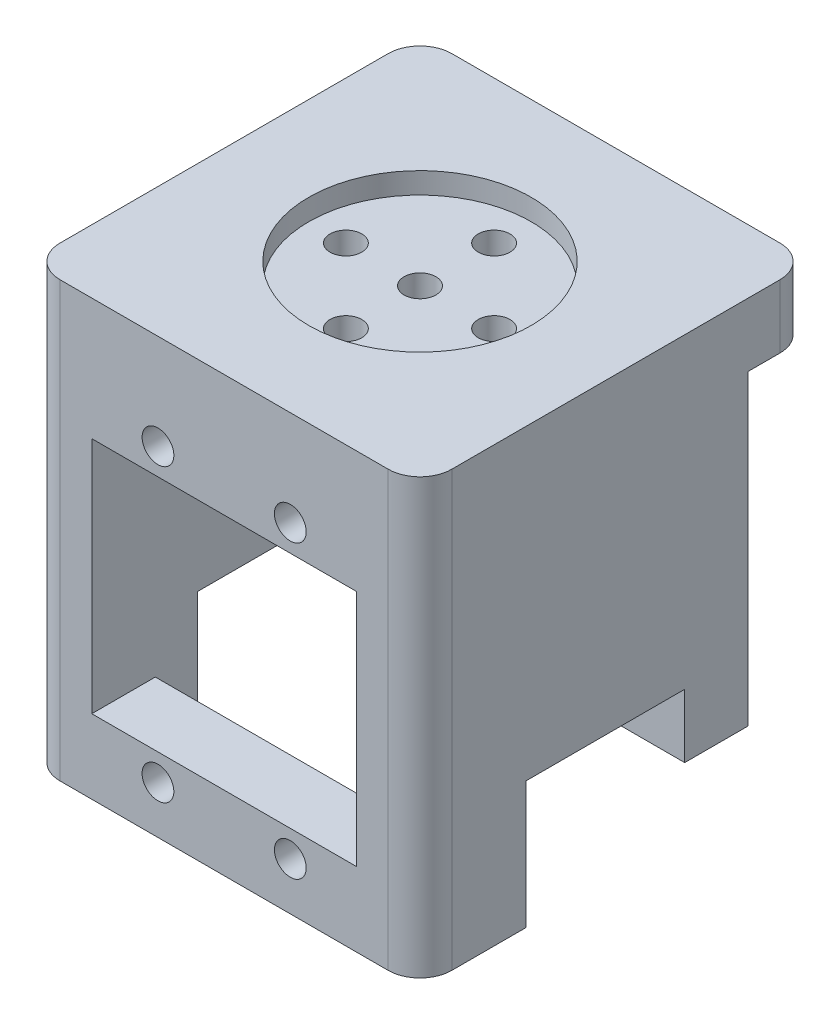
SolidWorks part; units mm, degrees
ref_plane "Front Plane" through (0, 0, 0) normal (0, 0, 1) x (1, 0, 0)
ref_plane "Top Plane" through (0, 0, 0) normal (0, 1, 0) x (1, 0, 0)
ref_plane "Right Plane" through (0, 0, 0) normal (1, 0, 0) x (0, 0, -1)
sketch "Sketch4" plane through (0, 0, 0) normal (0, 1, 0) x (1, 0, 0)
  line L0 (-11.8595, 7.7487) -> (-11.8595, -0.2513) construction
  line L5 (-11.8595, 7.7487) -> (13.1405, 7.7487)
  line L6 (-11.8595, 7.7487) -> (-11.8595, -17.2513)
  line L7 (-11.8595, -17.2513) -> (13.1405, -17.2513)
  line L8 (13.1405, 7.7487) -> (13.1405, -17.2513)
  line L9 (-11.8595, -0.2513) -> (13.1405, -0.2513) construction
  line L11 (-14.8595, 13.7487) -> (16.1405, 13.7487)
  line L12 (-17.8595, 10.7487) -> (-17.8595, -20.2513)
  line L13 (-14.8595, -23.2513) -> (16.1405, -23.2513)
  line L14 (19.1405, 10.7487) -> (19.1405, -20.2513)
  arc A3 (-17.8595, -20.2513) -> (-14.8595, -23.2513) centre (-14.8595, -20.2513) ccw
  arc A4 (16.1405, -23.2513) -> (19.1405, -20.2513) centre (16.1405, -20.2513) ccw
  arc A5 (16.1405, 13.7487) -> (19.1405, 10.7487) centre (16.1405, 10.7487) cw
  arc A6 (-14.8595, 13.7487) -> (-17.8595, 10.7487) centre (-14.8595, 10.7487) ccw
  point P14 (19.1405, -23.2513)
  point P16 (19.1405, 13.7487)
  point P18 (19.1405, 13.7487)
  point P19 (-17.8595, 13.7487)
  point P22 (-17.8595, 13.7487)
  dimension "D8" = 6
  dimension "D9" = 6
  dimension "D3" = 3
  dimension "D1" = 37
  dimension "D2" = 37
  dimension "D4" = 6
  dimension "D5" = 6
  dimension "D6" = 25
  dimension "D7" = 8
extrude "Boss-Extrude1" add sketch "Sketch4" along normal blind 35
sketch "Sketch22" plane through (-17.8595, 0, 0) normal (-1, 0, 0) x (0, 0, 1)
  line L0 (-13.7487, 35) -> (-13.7487, 0)
  line L1 (-13.7487, 35) -> (-13.7487, 0) construction
  line L2 (-13.7487, 0) -> (13.2513, 0)
  line L3 (-10.7487, 0) -> (20.2513, 0) construction
  line L4 (13.2513, 0) -> (13.2513, 12)
  line L5 (13.2513, 12) -> (-1.7487, 12)
  line L6 (-1.7487, 12) -> (-1.7487, 6)
  line L7 (-1.7487, 6) -> (-7.7487, 6)
  line L8 (-7.7487, 6) -> (-7.7487, 35)
  line L9 (-7.7487, 35) -> (-13.7487, 35)
  dimension "D1" = 35
  dimension "D2" = 6
  dimension "D3" = 6
  dimension "D4" = 15
  dimension "D5" = 12
  dimension "D6" = 6
extrude "Cut-Extrude12" cut sketch "Sketch22" against normal blind 50
sketch "Sketch23" plane through (0, 0, 23.2513) normal (0, 0, 1) x (1, 0, 0)
  line L0 (0.6405, 0) -> (-11.8595, 0) construction
  line L1 (-14.8595, 0) -> (16.1405, 0) construction
  line L2 (-11.8595, 0) -> (-11.8595, 34.5) construction
  line L3 (-11.8595, 34.5) -> (13.1405, 34.5) construction
  line L4 (13.1405, 34.5) -> (13.1405, 0) construction
  line L5 (13.1405, 0) -> (0.6405, 0) construction
  line L6 (-11.8595, 34.5) -> (-11.8595, 29.5) construction
  line L8 (-11.8595, 29.5) -> (13.1405, 29.5)
  line L9 (-11.8595, 29.5) -> (-11.8595, 7)
  line L10 (-11.8595, 7) -> (13.1405, 7)
  line L11 (13.1405, 29.5) -> (13.1405, 7)
  dimension "D1" = 12.5
  dimension "D2" = 12.5
  dimension "D3" = 34.5
  dimension "D4" = 5
  dimension "D5" = 22.5
extrude "Cut-Extrude13" cut sketch "Sketch23" against normal blind 7
sketch "Sketch24" plane through (0, 0, 0) normal (0, -1, 0) x (1, 0, 0)
  line L0 (19.1405, 13.2513) -> (13.1405, 13.2513) construction
  line L1 (-14.1391, 19.733) -> (16.7228, 19.733)
  line L2 (-14.1391, 19.733) -> (-14.1391, 13.2513)
  line L3 (-14.1391, 13.2513) -> (16.7228, 13.2513)
  line L4 (16.7228, 19.733) -> (16.7228, 13.2513)
extrude "Boss-Extrude6" add sketch "Sketch24" against normal blind 2
sketch "Sketch25" plane through (0, 0, -7.7487) normal (0, 0, -1) x (-1, 0, 0)
  line L0 (-16.1405, 6) -> (-16.1405, 11) construction
  line L1 (-19.1405, 6) -> (-13.1405, 6) construction
  line L2 (-16.1405, 11) -> (-16.1405, 14) construction
  line L3 (-16.1405, 14) -> (-16.1405, 20) construction
  line L4 (-16.1405, 20) -> (-16.1405, 23) construction
  line L7 (11.8595, 6) -> (17.8595, 6) construction
  line L8 (14.8595, 6) -> (14.8595, 11) construction
  line L9 (14.8595, 11) -> (14.8595, 14) construction
  line L10 (14.8595, 14) -> (14.8595, 20) construction
  line L11 (14.8595, 20) -> (14.8595, 21.5) construction
  line L12 (-16.1405, 23) -> (-16.1405, 29) construction
  line L13 (-16.1405, 29) -> (-16.1405, 32) construction
  line L14 (14.8595, 21.5) -> (14.8595, 23) construction
  line L15 (14.8595, 23) -> (14.8595, 29) construction
  line L16 (14.8595, 29) -> (14.8595, 32) construction
  circle A0 centre (-16.1405, 21.5) radius 1.5
  circle A1 centre (-16.1405, 17) radius 1.5
  circle A2 centre (-16.1405, 12.5) radius 1.5
  circle A3 centre (14.8595, 12.5) radius 1.5
  circle A4 centre (14.8595, 21.5) radius 1.5
  circle A5 centre (14.8595, 17) radius 1.5
  circle A7 centre (14.8595, 30.5) radius 1.5
  circle A8 centre (-16.1405, 30.5) radius 1.5
  circle A10 centre (-16.1405, 26) radius 1.5
  circle A11 centre (14.8595, 26) radius 1.5
  dimension "D5" = 3
  dimension "D11" = 3
  dimension "D15" = 3
  dimension "D16" = 3
  dimension "D1" = 5
  dimension "D2" = 3
  dimension "D3" = 6
  dimension "D4" = 3
  dimension "D7" = 5
  dimension "D8" = 3
  dimension "D9" = 6
  dimension "D10" = 6
  dimension "D12" = 6
  dimension "D13" = 3
  dimension "D14" = 3
extrude "Cut-Extrude14" cut sketch "Sketch25" against normal blind 3.5
sketch "Sketch26" plane through (0, 6, 0) normal (0, -1, 0) x (1, 0, 0)
  line L0 (19.1405, -7.7487) -> (13.1405, -1.7487) construction
  line L1 (-11.8595, -7.7487) -> (-17.8595, -1.7487) construction
  circle A0 centre (-14.8595, -4.7487) radius 1.5
  circle A1 centre (16.1405, -4.7487) radius 1.5
  dimension "D1" = 3
  dimension "D2" = 3
extrude "Cut-Extrude15" cut sketch "Sketch26" against normal blind 3.5
sketch "Sketch27" plane through (0, 35, 0) normal (0, 1, 0) x (1, 0, 0)
  line L0 (19.1405, -20.2513) -> (19.1405, 7.7487) construction
  line L1 (-14.8595, -23.2513) -> (16.1405, -23.2513)
  line L2 (-17.8595, -20.2513) -> (-17.8595, 10.7487)
  line L3 (-14.8595, 13.7487) -> (16.1405, 13.7487)
  line L4 (19.1405, -20.2513) -> (19.1405, 10.7487)
  arc A0 (-14.8595, -23.2513) -> (-17.8595, -20.2513) centre (-14.8595, -20.2513) cw
  arc A1 (16.1405, -23.2513) -> (19.1405, -20.2513) centre (16.1405, -20.2513) ccw
  arc A2 (16.1405, 13.7487) -> (19.1405, 10.7487) centre (16.1405, 10.7487) cw
  arc A3 (-17.8595, 10.7487) -> (-14.8595, 13.7487) centre (-14.8595, 10.7487) cw
  point P8 (-17.8595, -23.2513)
  point P11 (19.1405, -23.2513)
  point P14 (19.1405, 13.7487)
  dimension "D2" = 3
  dimension "D1" = 37
extrude "Boss-Extrude8" add sketch "Sketch27" along normal blind 6
sketch "Sketch28" plane through (0, 0, 23.2513) normal (0, 0, 1) x (1, 0, 0)
  line L0 (-11.8595, 29.5) -> (-11.8595, 34.5) construction
  line L1 (-11.8595, 34.5) -> (0.6405, 34.5) construction
  line L2 (0.6405, 34.5) -> (0.6405, 29.5) construction
  line L3 (13.1405, 29.5) -> (-11.8595, 29.5) construction
  line L4 (13.1405, 29.5) -> (13.1405, 34.5) construction
  line L5 (13.1405, 34.5) -> (0.6405, 34.5) construction
  line L6 (0.6405, 34.5) -> (0.6405, 29.5) construction
  line L7 (-11.8595, 34.5) -> (0.6405, 29.5) construction
  line L8 (0.6405, 34.5) -> (13.1405, 29.5) construction
  line L9 (-11.8595, 7) -> (-11.8595, 2) construction
  line L10 (-11.8595, 2) -> (0.6405, 2) construction
  line L11 (0.6405, 2) -> (0.6405, 7) construction
  line L12 (-11.8595, 7) -> (13.1405, 7) construction
  line L13 (13.1405, 7) -> (13.1405, 2) construction
  line L14 (13.1405, 2) -> (0.6405, 2) construction
  line L15 (-11.8595, 7) -> (0.6405, 2) construction
  line L16 (0.6405, 2) -> (13.1405, 7) construction
  circle A0 centre (-5.6095, 32) radius 1.5
  circle A1 centre (6.8905, 32) radius 1.5
  circle A2 centre (-5.6095, 4.5) radius 1.5
  circle A3 centre (6.8905, 4.5) radius 1.5
  dimension "D5" = 3
  dimension "D6" = 3
  dimension "D9" = 3
  dimension "D10" = 3
  dimension "D1" = 12.5
  dimension "D2" = 5
  dimension "D3" = 5
  dimension "D4" = 12.5
  dimension "D7" = 5
  dimension "D8" = 12.5
extrude "Cut-Extrude16" cut sketch "Sketch28" against normal blind 10
sketch "Sketch29" plane through (0, 41, 0) normal (0, 1, 0) x (1, 0, 0)
  line L0 (-16.9809, 12.87) -> (18.2618, -22.3726) construction
  arc A0 (-14.8595, 13.7487) -> (-17.8595, 10.7487) centre (-14.8595, 10.7487) ccw construction
  arc A1 (16.1405, -23.2513) -> (19.1405, -20.2513) centre (16.1405, -20.2513) ccw construction
  circle A2 centre (0.6405, -4.7513) radius 7 construction
  circle A3 centre (0.6405, 2.2487) radius 1.5
  circle A4 centre (7.6405, -4.7513) radius 1.5
  circle A5 centre (0.6405, -11.7513) radius 1.5
  circle A6 centre (-6.3595, -4.7513) radius 1.5
  circle A7 centre (0.6405, -4.7513) radius 1.5
  dimension "D1" = 14
  dimension "D2" = 3
extrude "Cut-Extrude17" cut sketch "Sketch29" against normal blind 10
sketch "Sketch30" plane through (0, 41, 0) normal (0, 1, 0) x (1, 0, 0)
  circle A0 centre (0.6405, -4.7513) radius 10.5
  dimension "D1" = 21
extrude "Cut-Extrude18" cut sketch "Sketch30" against normal blind 2
